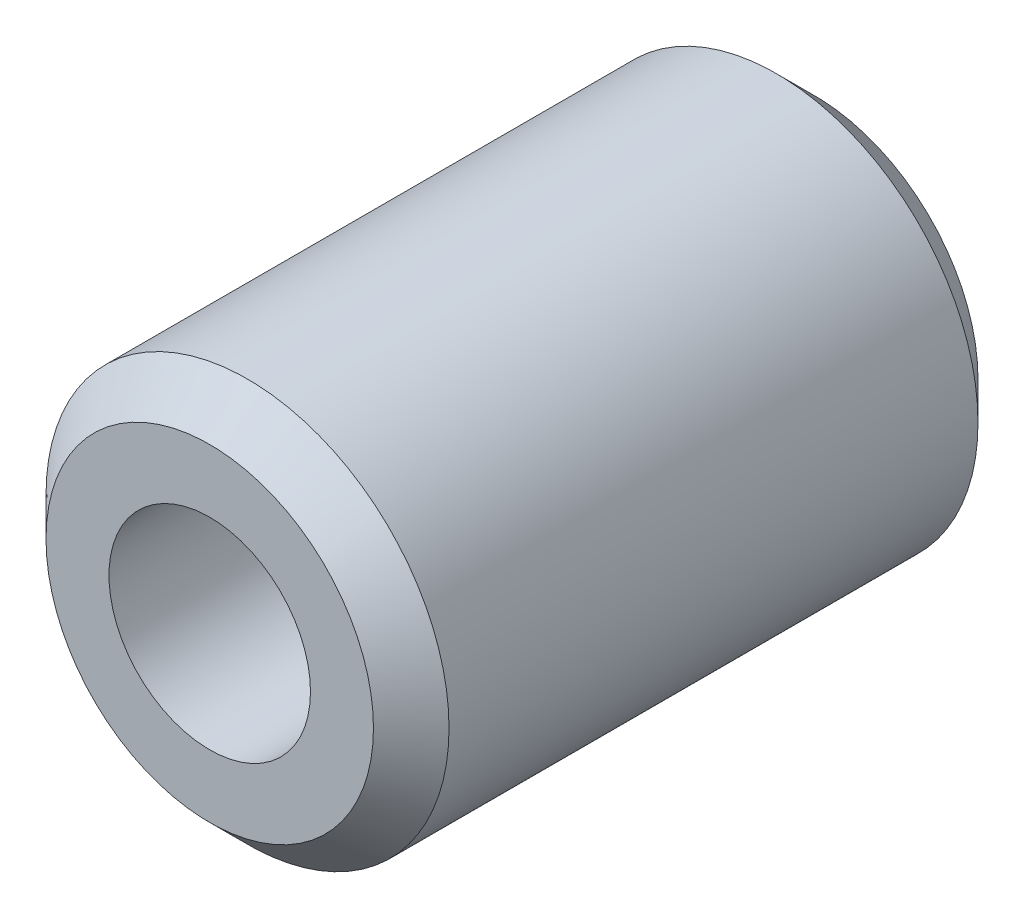
SolidWorks part; units mm, degrees
ref_plane "Front Plane" through (0, 0, 0) normal (0, 0, 1) x (1, 0, 0)
ref_plane "Top Plane" through (0, 0, 0) normal (0, 1, 0) x (1, 0, 0)
ref_plane "Right Plane" through (0, 0, 0) normal (1, 0, 0) x (0, 0, -1)
sketch "Sketch1" plane through (0, 0, 0) normal (1, 0, 0) x (0, 0, -1)
  line L0 (-4.7625, 0) -> (4.7625, 0) construction
  line L1 (4.7625, 3.175) -> (4.7625, -3.175) construction
  line L2 (-4.7625, 3.175) -> (-4.7625, -3.175) construction
  line L3 (4.7625, 3.175) -> (-4.7625, 3.175) construction
  line L4 (4.7625, -3.175) -> (-4.7625, -3.175) construction
  line L5 (-4.7625, 1.5875) -> (4.7625, 1.5875) construction
  line L6 (-4.7625, -1.5875) -> (4.7625, -1.5875) construction
  point P2 (0, 0)
  point P7 (-4.7625, 0)
  point P8 (-4.7625, -1.5875)
  point P9 (4.7625, 0)
  point P11 (-4.7625, 1.5875)
  dimension "OD" = 6.35
  dimension "ID" = 3.175
  dimension "Length" = 9.525
sketch "Sketch2" plane through (0, 0, 0) normal (0, 0, 1) x (1, 0, 0)
  line L0 (-3.175, 0) -> (3.175, 0) construction
  line L1 (0, -3.175) -> (0, 3.175) construction
  circle A0 centre (0, 0) radius 1.5875 construction
  circle A1 centre (0, 0) radius 3.175 construction
  point P16 (0, 0)
  dimension "ID" = 3.175
  dimension "OD" = 6.35
sketch "Sketch3" plane through (0, 0, 0) normal (1, 0, 0) x (0, 0, -1)
  line L0 (-4.7625, 1.5875) -> (4.7625, 1.5875)
  line L1 (4.7625, 3.175) -> (4.7625, -3.175) construction
  line L2 (4.7625, 1.5875) -> (4.7625, 3.175)
  line L5 (4.7625, 3.175) -> (-4.7625, 3.175)
  line L6 (-4.7625, 3.175) -> (-4.7625, 1.5875)
  line L7 (-4.7625, 0) -> (4.7625, 0) construction
revolve "Revolve1" add sketch "Sketch3" angle 360 about L7
chamfer "Chamfer1" distance 0.5953 angle 45 2 edges at (3.175, 0, 4.7625) (3.175, 0, -4.7625)
equation "\"D1@Chamfer1\"=((\"OD@Sketch1\"-\"ID@Sketch1\")/2)*.375"
